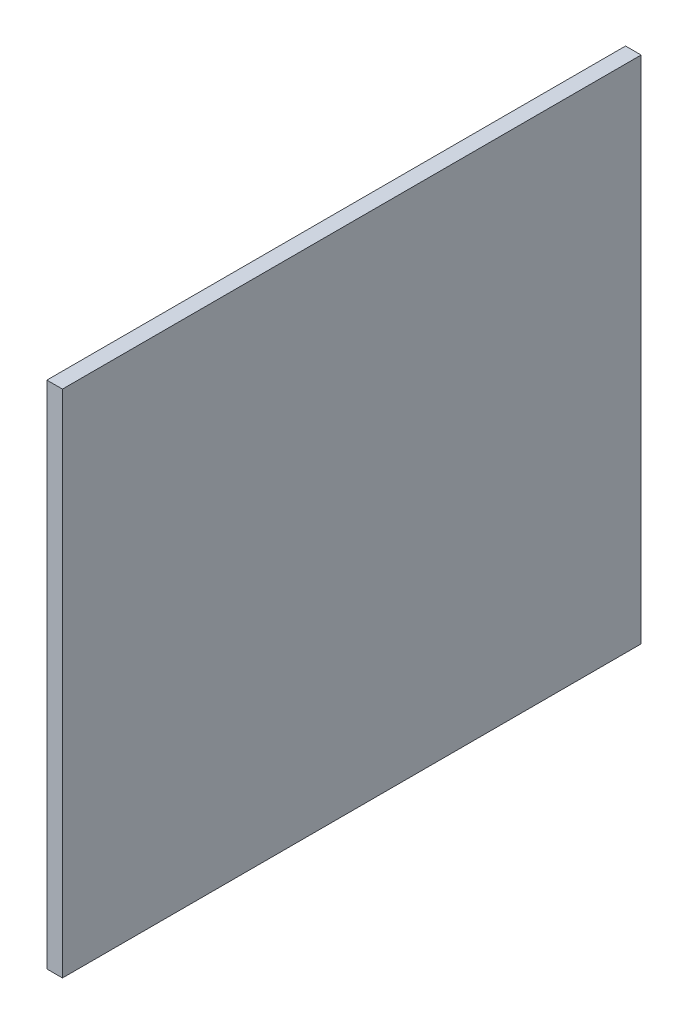
SolidWorks part; units mm, degrees
ref_plane "Front" through (0, 0, 0) normal (0, 0, 1) x (1, 0, 0)
ref_plane "Top" through (0, 0, 0) normal (0, 1, 0) x (1, 0, 0)
ref_plane "Right" through (0, 0, 0) normal (1, 0, 0) x (0, 0, -1)
sketch "Sketch1" plane through (0, 0, 0) normal (1, 0, 0) x (0, 0, -1)
  line L1 (-59, 52) -> (59, 52)
  line L2 (-59, 52) -> (-59, -52)
  line L3 (-59, -52) -> (59, -52)
  line L4 (59, 52) -> (59, -52)
  line L5 (-59, 52) -> (59, -52) construction
  line L6 (-59, -52) -> (59, 52) construction
  point P0 (0, 0)
  dimension "D1" = 104
  dimension "D2" = 118
extrude "Boss-Extrude1" add sketch "Sketch1" along normal blind 3.175
